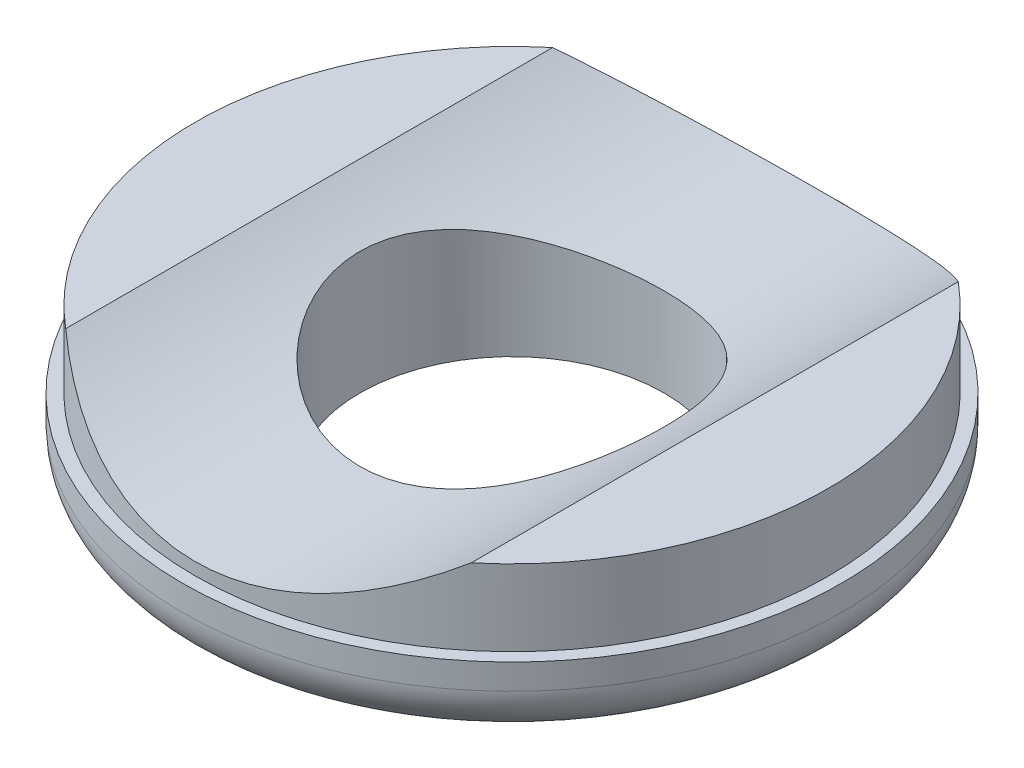
SolidWorks part; units mm, degrees
ref_plane "前视基准面" through (0, 0, 0) normal (0, 0, 1) x (1, 0, 0)
ref_plane "上视基准面" through (0, 0, 0) normal (0, 1, 0) x (1, 0, 0)
ref_plane "右视基准面" through (0, 0, 0) normal (1, 0, 0) x (0, 0, -1)
other "Configuration Table"
sketch "草图1" plane through (0, 0, 0) normal (0, 1, 0) x (1, 0, 0)
  circle A0 centre (0, 0) radius 6.5
  dimension "D1" = 13
extrude "凸台-拉伸1" add sketch "草图1" along normal blind 1.5
fillet "圆角1" radius 1 1 edges at (0, 0, 6.5)
sketch "草图2" plane through (0, 1.5, 0) normal (0, 1, 0) x (1, 0, 0)
  circle A2 centre (0, 0) radius 6.25
  circle A3 centre (0, 0) radius 6.25
  dimension "D1" = 0.25
extrude "凸台-拉伸2" add sketch "草图2" along normal blind 1.5
sketch "草图3" plane through (0, 0, 0) normal (0, 0, 1) x (1, 0, 0)
  line L0 (0, 0) -> (0, 50000) construction
  line L1 (6.25, 3) -> (-6.25, 3) construction
  line L3 (6.25, 3) -> (-6.25, 3)
  arc A0 (-4, 3) -> (4, 3) centre (0, 8.7446) ccw
  point P8 (0, 12.5562)
  point P9 (0, 0)
  point P10 (0, 14.8754)
  point P11 (-5.6294, 3)
  point P12 (4.0658, 3)
  dimension "D1" = 2.25
  dimension "14" = 7
extrude "切除-拉伸1" cut sketch "草图3" against normal through all both and the other way through all contours A0 L0 L3 | L0 A0 L3
sketch "草图4" plane through (0, 0, 0) normal (0, -1, 0) x (1, 0, 0)
  circle A0 centre (0, 0) radius 3
  dimension "D1" = 6
extrude "切除-拉伸2" cut sketch "草图4" against normal through all
